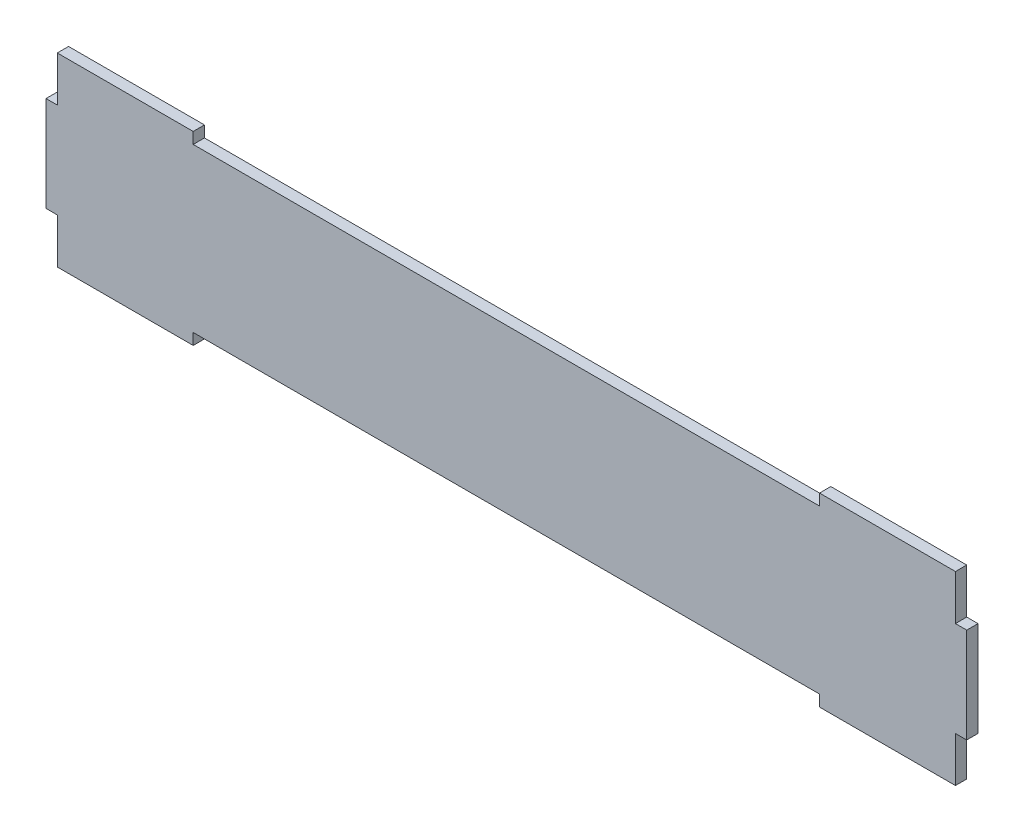
SolidWorks part; units mm, degrees
ref_plane "Front Plane" through (0, 0, 0) normal (0, 0, 1) x (1, 0, 0)
ref_plane "Top Plane" through (0, 0, 0) normal (0, 1, 0) x (1, 0, 0)
ref_plane "Right Plane" through (0, 0, 0) normal (1, 0, 0) x (0, 0, -1)
sketch "Sketch1" plane through (0, 0, 0) normal (0, 0, 1) x (1, 0, 0)
  line L1 (0, 0) -> (490, 0)
  line L2 (0, 0) -> (0, 98.65)
  line L3 (0, 98.65) -> (490, 98.65)
  line L4 (490, 0) -> (490, 98.65)
  dimension "D1" = 490
  dimension "D2" = 98.65
extrude "Boss-Extrude1" add sketch "Sketch1" along normal blind 6
sketch "Sketch2" plane through (0, 0, 6) normal (0, 0, 1) x (1, 0, 0)
  line L0 (490, 98.65) -> (0, 98.65) construction
  line L1 (490, 98.65) -> (484, 98.65)
  line L2 (490, 98.65) -> (490, 74.65)
  line L3 (490, 74.65) -> (484, 74.65)
  line L4 (484, 98.65) -> (484, 74.65)
  line L5 (490, 0) -> (484, 0)
  line L6 (490, 0) -> (490, 24)
  line L7 (490, 24) -> (484, 24)
  line L8 (484, 0) -> (484, 24)
  line L9 (0, 0) -> (6, 0)
  line L10 (0, 0) -> (0, 24)
  line L11 (0, 24) -> (6, 24)
  line L12 (6, 0) -> (6, 24)
  line L13 (0, 98.65) -> (6, 98.65)
  line L14 (0, 98.65) -> (0, 74.65)
  line L15 (0, 74.65) -> (6, 74.65)
  line L16 (6, 98.65) -> (6, 74.65)
  line L17 (78.3333, 98.65) -> (411.6667, 98.65)
  line L18 (78.3333, 98.65) -> (78.3333, 92.65)
  line L19 (78.3333, 92.65) -> (411.6667, 92.65)
  line L20 (411.6667, 98.65) -> (411.6667, 92.65)
  line L22 (0, 0) -> (490, 0) construction
  line L23 (78.3333, 0) -> (411.6667, 0)
  line L24 (78.3333, 0) -> (78.3333, 6)
  line L25 (78.3333, 6) -> (411.6667, 6)
  line L26 (411.6667, 0) -> (411.6667, 6)
  point P26 (245, 98.65)
  point P27 (245, 0)
  dimension "D1" = 6
  dimension "D2" = 24
  dimension "D3" = 6
  dimension "D4" = 24
  dimension "D5" = 24
  dimension "D6" = 6
  dimension "D7" = 6
  dimension "D8" = 24
  dimension "D9" = 333.3333
  dimension "D10" = 245
  dimension "D11" = 333.3333
  dimension "D12" = 6
  dimension "D13" = 6
  dimension "D14" = 245
extrude "Cut-Extrude1" cut sketch "Sketch2" against normal through all
